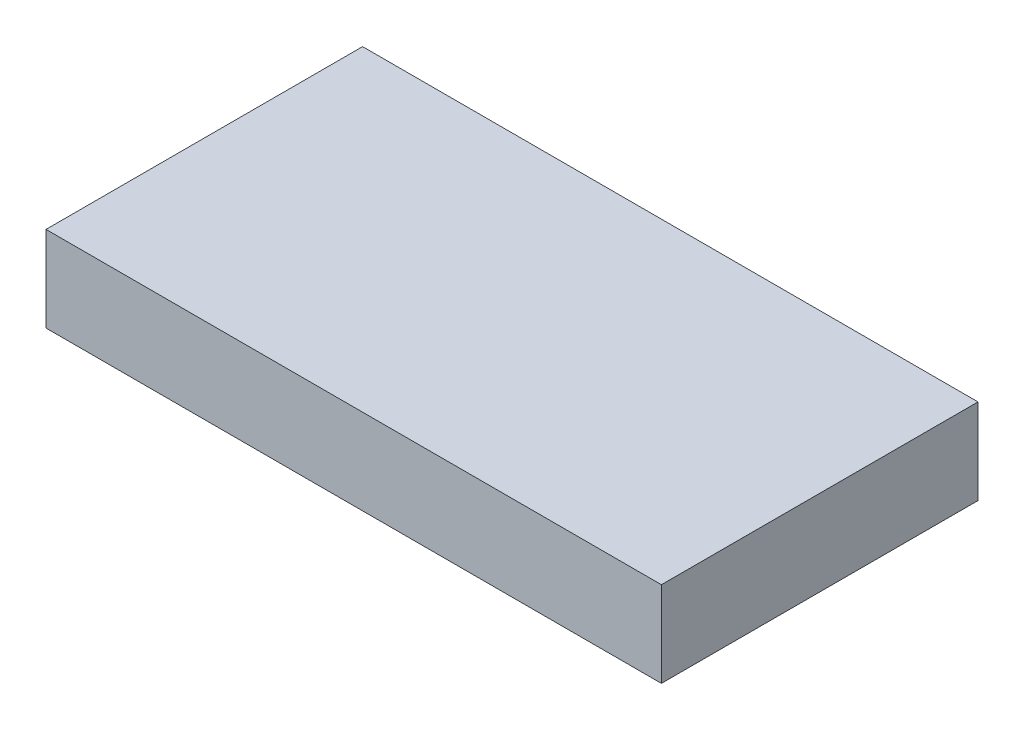
SolidWorks part; units mm, degrees
ref_plane "Front Plane" through (0, 0, 0) normal (0, 0, 1) x (1, 0, 0)
ref_plane "Top Plane" through (0, 0, 0) normal (0, 1, 0) x (1, 0, 0)
ref_plane "Right Plane" through (0, 0, 0) normal (1, 0, 0) x (0, 0, -1)
sketch "Sketch1" plane through (0, 0, 0) normal (0, 1, 0) x (1, 0, 0)
  line L1 (0, 0) -> (228.6, 0)
  line L2 (0, 0) -> (0, 117.602)
  line L3 (0, 117.602) -> (228.6, 117.602)
  line L4 (228.6, 0) -> (228.6, 117.602)
  dimension "D1" = 228.6
  dimension "D2" = 117.602
extrude "Boss-Extrude1" add sketch "Sketch1" along normal blind 31.75
